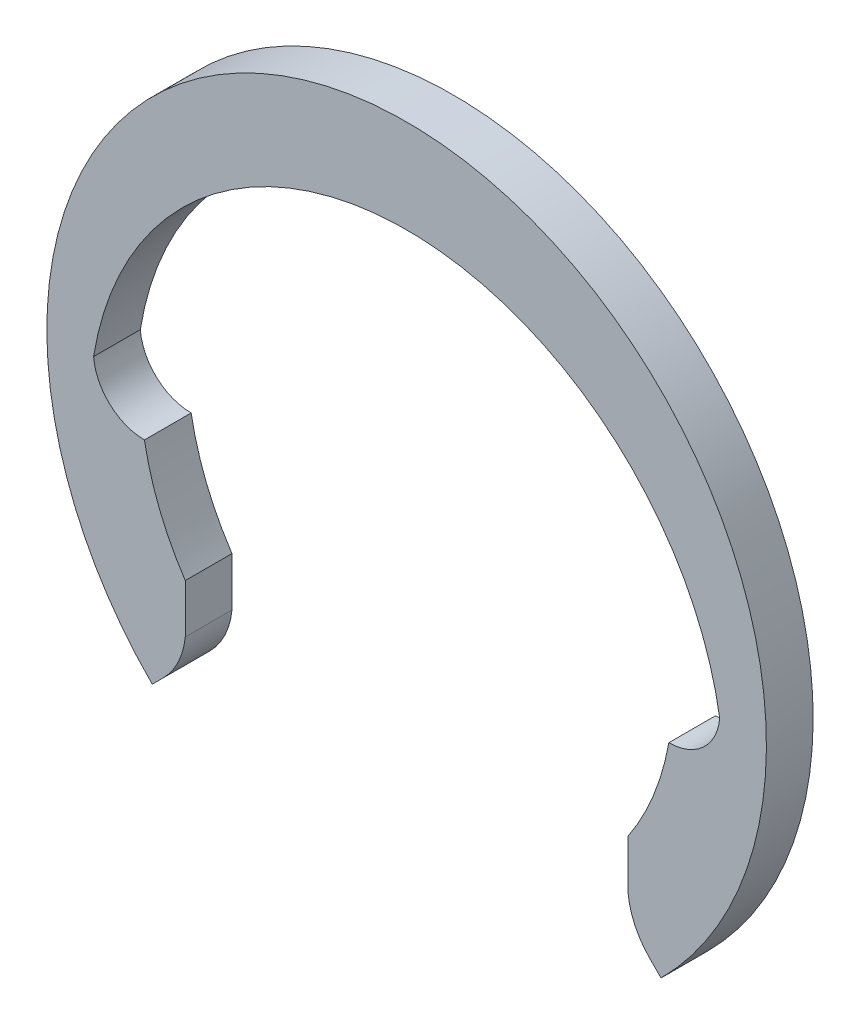
SolidWorks part; units mm, degrees
ref_plane "Front" through (0, 0, 0) normal (0, 0, 1) x (1, 0, 0)
ref_plane "Top" through (0, 0, 0) normal (0, 1, 0) x (1, 0, 0)
ref_plane "Right" through (0, 0, 0) normal (1, 0, 0) x (0, 0, -1)
sketch "Layout" plane through (0, 0, 0) normal (0, 0, 1) x (1, 0, 0)
  line L0 (0, 7.7) -> (0, -7.7) construction
  line L1 (-5.7, 0) -> (-7.7, 0) construction
  line L2 (-7.7, 0) -> (-8.7, 0) construction
  line L3 (-5.7, 0) -> (5.7, 0) construction
  line L4 (-4.7376, -4.7376) -> (-4.7376, -3.1694) construction
  line L5 (-5.6116, -1) -> (5.6116, -1) construction
  line L6 (-5.7, 0) -> (-5.7, -1) construction
  line L7 (0, 0) -> (-4.0305, -4.0305) construction
  line L8 (-4.0305, -4.0305) -> (-5.4447, -5.4447) construction
  circle A0 centre (0, 0) radius 7.7 construction
  circle A1 centre (0, 0) radius 5.7 construction
  arc A2 (0, 5.7) -> (-6.7, 0) centre (0, -1.0877) ccw construction
  circle A3 centre (0, 0) radius 7.9 construction
  arc A4 (-6.7, 0) -> (-5.6116, -1) centre (-5.6116, 0.0923) ccw construction
  dimension "D1" = 45
  dimension "RingOD" = 15.4
  dimension "D3" = 11.4
  dimension "Clear Dia" = 15.8
  dimension "Cad E" = 2
  dimension "thickness" = 1
sketch "Sketch2" plane through (0, 0, 0) normal (0, 0, 1) x (1, 0, 0)
  line L0 (-4.7376, -4.7376) -> (-4.7376, -4.2149) construction
  line L1 (-4.7376, -4.2149) -> (-4.7376, -3.6921)
  line L2 (-4.7376, -3.6921) -> (-4.7376, -3.1694)
  line L4 (0, 7.7) -> (0, -7.7) construction
  line L5 (-4.7376, -4.7376) -> (-4.9733, -4.9733) construction
  line L6 (0, 7.7) -> (0, 5.7) construction
  line L7 (-4.9733, -4.9733) -> (-5.209, -5.209) construction
  line L8 (-5.209, -5.209) -> (-5.4447, -5.4447)
  line L9 (-4.0305, -4.0305) -> (-5.4447, -5.4447) construction
  line L10 (4.7376, -3.6921) -> (4.7376, -3.1694)
  line L11 (4.7376, -4.2149) -> (4.7376, -3.6921)
  line L12 (5.209, -5.209) -> (5.4447, -5.4447)
  circle A0 centre (0, 0) radius 7.7 construction
  arc A1 (0, 5.7) -> (-6.7, 0) centre (0, -1.0877) ccw construction
  arc A2 (-6.7, 0) -> (-5.6116, -1) centre (-5.6116, 0.0923) ccw construction
  circle A3 centre (0, 0) radius 5.7 construction
  arc A4 (5.4447, -5.4447) -> (-5.4447, -5.4447) centre (0, 0) ccw
  arc A5 (6.7, 0) -> (-6.7, 0) centre (0, -1.0877) ccw
  arc A6 (-6.7, 0) -> (-5.6116, -1) centre (-5.6116, 0.0923) ccw
  arc A7 (-5.6116, -1) -> (-4.7376, -3.1694) centre (0, 0) ccw
  arc A8 (-4.7376, -4.2149) -> (-5.209, -5.209) centre (-6.3669, -4.0511) cw
  arc A9 (4.7376, -4.2149) -> (5.209, -5.209) centre (6.3669, -4.0511) ccw
  arc A10 (5.6116, -1) -> (4.7376, -3.1694) centre (0, 0) cw
  arc A11 (6.7, 0) -> (5.6116, -1) centre (5.6116, 0.0923) cw
extrude "Boss-Extrude1" add sketch "Sketch2" along normal blind 1
equation "\"D1@Boss-Extrude1\"=\"thickness@Layout\""
